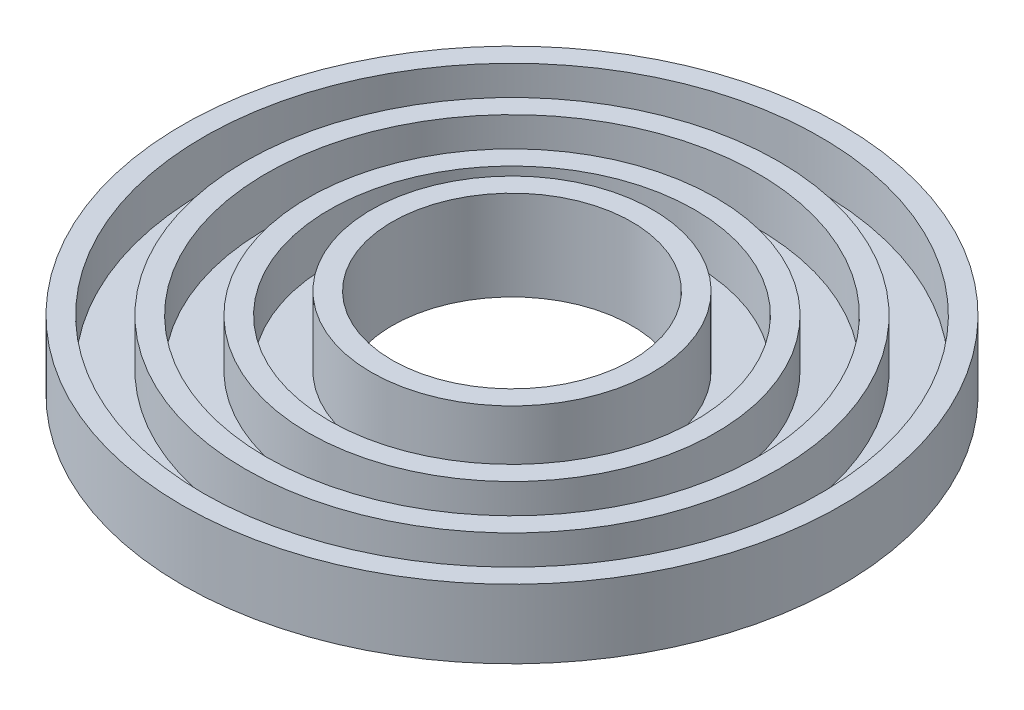
SolidWorks part; units mm, degrees
ref_plane "Alzado" through (0, 0, 0) normal (0, 0, 1) x (1, 0, 0)
ref_plane "Planta" through (0, 0, 0) normal (0, 1, 0) x (1, 0, 0)
ref_plane "Vista lateral" through (0, 0, 0) normal (1, 0, 0) x (0, 0, -1)
sketch "Croquis1" plane through (0, 0, 0) normal (0, 1, 0) x (1, 0, 0)
  circle A0 centre (0, 0) radius 11
  circle A1 centre (0, 0) radius 4
  dimension "D1" = 22
  dimension "D2" = 8
extrude "Extruir1" add sketch "Croquis1" along normal blind 0.7
sketch "Croquis2" plane through (0, 0.7, 0) normal (0, 1, 0) x (1, 0, 0)
  line L0 (0, 4.7) -> (0, 6.1) construction
  line L1 (0, 6.8) -> (0, 8.2) construction
  line L2 (0, 8.9) -> (0, 10.3) construction
  circle A0 centre (0, 0) radius 10.3
  circle A1 centre (0, 0) radius 11
  circle A2 centre (0, 0) radius 11
  circle A3 centre (0, 0) radius 4 construction
  circle A4 centre (0, 0) radius 4
  circle A5 centre (0, 0) radius 4.7
  circle A6 centre (0, 0) radius 6.1
  circle A7 centre (0, 0) radius 6.8
  circle A8 centre (0, 0) radius 8.2
  circle A9 centre (0, 0) radius 8.9
  circle M2 centre (0, 0) radius 11
  circle M3 centre (0, 0) radius 4
  dimension "D3" = 0.7
  dimension "D4" = 0.7
  dimension "D5" = 0.7
  dimension "D1" = 0
  dimension "D2" = 0.7
extrude "Extruir2" add sketch "Croquis2" along normal blind 1.6 contours A0 M2 | A9 A8 | A7 A6 | A5 M3
sketch "Croquis3" plane through (0, 2.3, 0) normal (0, 1, 0) x (1, 0, 0)
  circle A0 centre (0, 0) radius 4 construction
  circle A1 centre (0, 0) radius 4.7
  circle A2 centre (0, 0) radius 4.7
  circle A3 centre (0, 0) radius 4
  dimension "D1" = 0
extrude "Extruir3" add sketch "Croquis3" along normal offset from surface (0.7 mm away) 3 up to face at (0, 0, 11)
